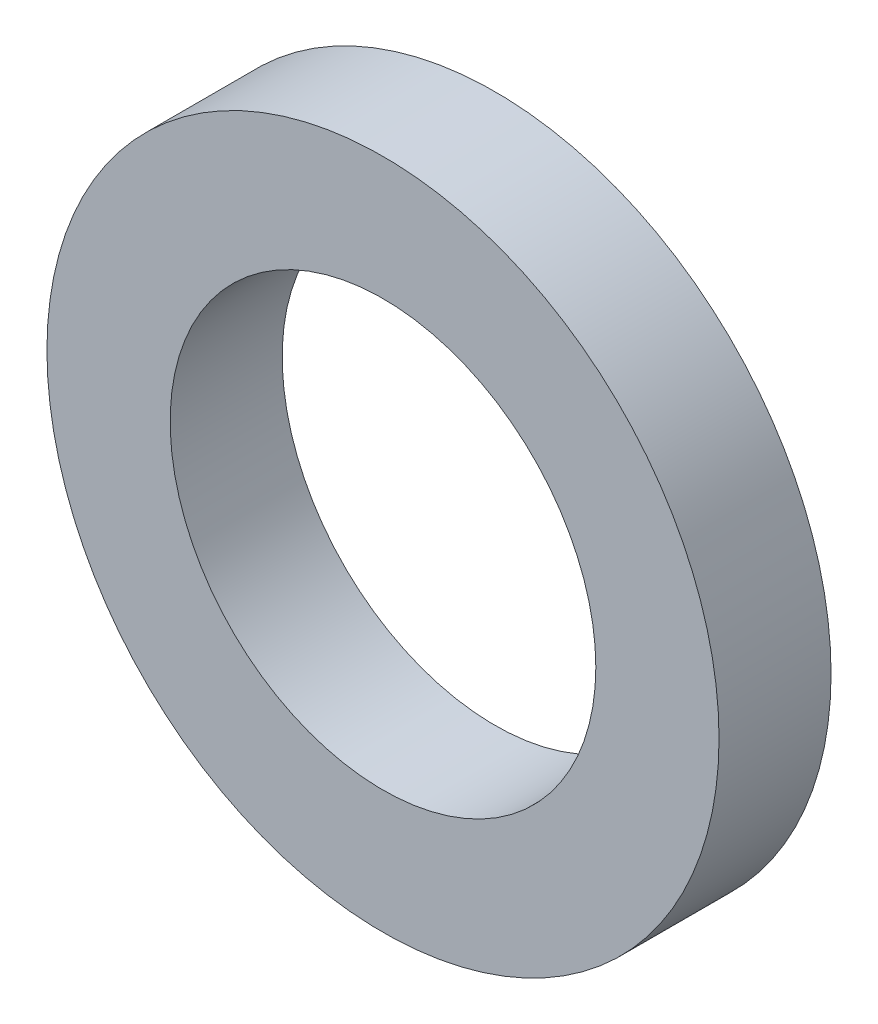
SolidWorks part; units mm, degrees
material "1023 Carbon Steel Sheet (SS)"
ref_plane "Front Plane" through (0, 0, 0) normal (0, 0, 1) x (1, 0, 0)
ref_plane "Top Plane" through (0, 0, 0) normal (0, 1, 0) x (1, 0, 0)
ref_plane "Right Plane" through (0, 0, 0) normal (1, 0, 0) x (0, 0, -1)
sketch "Sketch1" plane through (0, 0, 0) normal (0, 0, 1) x (1, 0, 0)
  circle A0 centre (0, 0) radius 1.9
  circle A1 centre (0, 0) radius 3
  dimension "D1" = 3.8
  dimension "D2" = 6
extrude "Boss-Extrude1" add sketch "Sketch1" along normal mid plane 1
